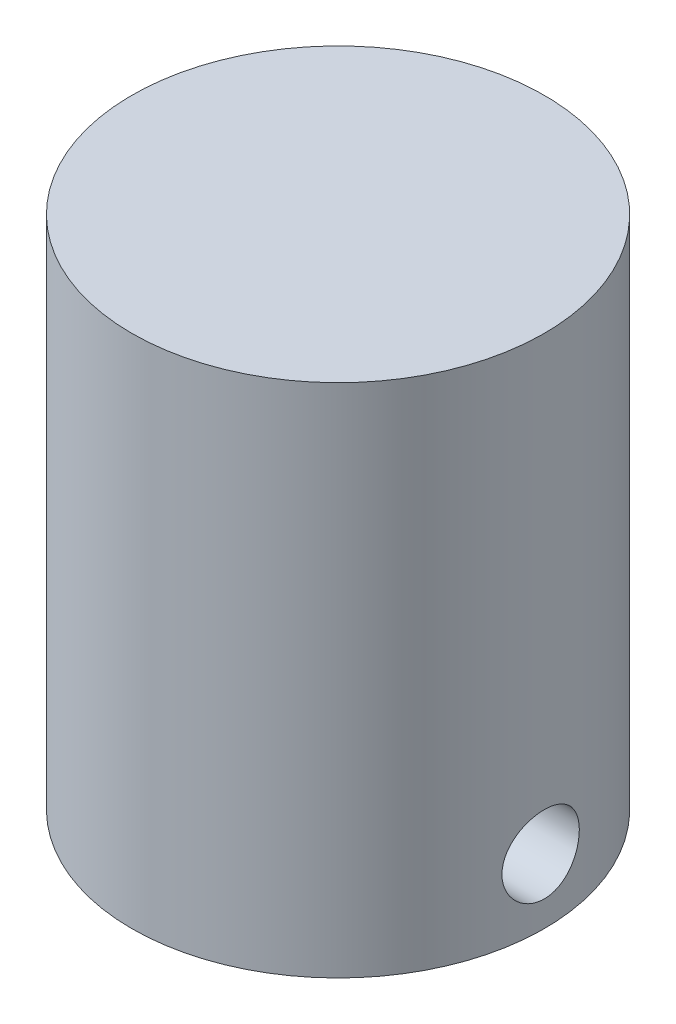
SolidWorks part; units mm, degrees
ref_plane "Front Plane" through (0, 0, 0) normal (0, 0, 1) x (1, 0, 0)
ref_plane "Top Plane" through (0, 0, 0) normal (0, 1, 0) x (1, 0, 0)
ref_plane "Right Plane" through (0, 0, 0) normal (1, 0, 0) x (0, 0, -1)
sketch "Sketch3" plane through (0, 0, 0) normal (0, 1, 0) x (1, 0, 0)
  circle A0 centre (0, 0) radius 8
  dimension "D1" = 16
extrude "Boss-Extrude1" add sketch "Sketch3" along normal blind 20
sketch "Sketch4" plane through (0, 0, 0) normal (0, -1, 0) x (1, 0, 0)
  circle A0 centre (0, 0) radius 4
  dimension "D1" = 8
extrude "Cut-Extrude1" cut sketch "Sketch4" against normal blind 12
sketch "Sketch5" plane through (0, 0, 0) normal (1, 0, 0) x (0, 0, -1)
  circle A0 centre (0, 2.5) radius 1.5
  dimension "D1" = 3
  dimension "D2" = 2.5
extrude "Cut-Extrude2" cut sketch "Sketch5" against normal through all both and the other way through all
